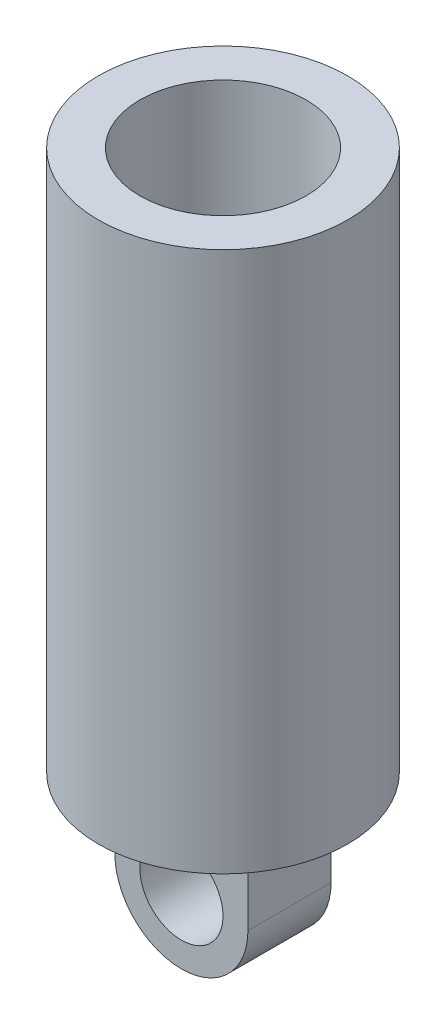
SolidWorks part; units mm, degrees
ref_plane "Front Plane" through (0, 0, 0) normal (0, 0, 1) x (1, 0, 0)
ref_plane "Top Plane" through (0, 0, 0) normal (0, 1, 0) x (1, 0, 0)
ref_plane "Right Plane" through (0, 0, 0) normal (1, 0, 0) x (0, 0, -1)
sketch "Sketch1" plane through (0, 0, 0) normal (0, 0, 1) x (1, 0, 0)
  line L2 (-4, 0) -> (-4, 5)
  line L3 (-4, 5) -> (4, 5)
  line L4 (4, 0) -> (4, 5)
  line L7 (-2.5, 5) -> (2.5, 5)
  circle A0 centre (0, 0) radius 2.5
  arc A1 (-4, 0) -> (4, 0) centre (0, 0) ccw
  dimension "D1" = 5
  dimension "D2" = 8
  dimension "D3" = 5
extrude "Boss-Extrude1" add sketch "Sketch1" along normal mid plane 5 contours L2 A1 L4 L3 A0
sketch "Sketch2" plane through (0, 5, 0) normal (0, 1, 0) x (1, 0, 0)
  circle A0 centre (0, 0) radius 7.5
  dimension "D1" = 15
extrude "Boss-Extrude2" add sketch "Sketch2" along normal blind 2.5
sketch "Sketch3" plane through (0, 7.5, 0) normal (0, 1, 0) x (1, 0, 0)
  circle A0 centre (0, 0) radius 5
  circle A1 centre (0, 0) radius 7.5
  circle A2 centre (0, 0) radius 7.5 construction
  dimension "D1" = 10
extrude "Boss-Extrude4" add sketch "Sketch3" along normal blind 30
